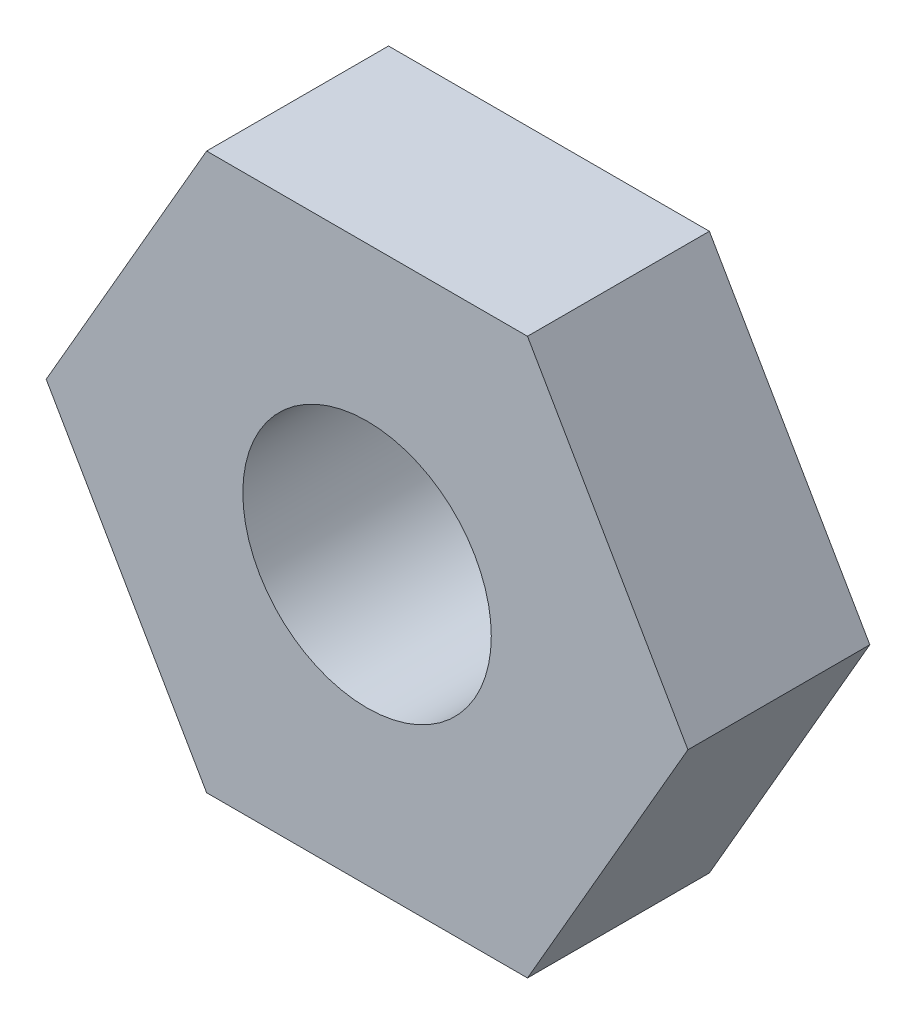
SolidWorks part; units mm, degrees
ref_plane "Front" through (0, 0, 0) normal (0, 0, 1) x (1, 0, 0)
ref_plane "Top" through (0, 0, 0) normal (0, 1, 0) x (1, 0, 0)
ref_plane "Right" through (0, 0, 0) normal (1, 0, 0) x (0, 0, -1)
sketch "Sketch1" plane through (0, 0, 0) normal (0, 0, 1) x (1, 0, 0)
  line L1 (1.5877, -2.75) -> (3.1754, 0)
  line L2 (3.1754, 0) -> (1.5877, 2.75)
  line L3 (1.5877, 2.75) -> (-1.5877, 2.75)
  line L4 (-1.5877, 2.75) -> (-3.1754, 0)
  line L5 (-3.1754, 0) -> (-1.5877, -2.75)
  line L6 (-1.5877, -2.75) -> (1.5877, -2.75)
  circle A0 centre (0, 0) radius 2.75 construction
  circle A1 centre (0, 0) radius 1.2295
  dimension "D1" = 2.459
  dimension "s" = 5.5
extrude "BaseNut" add sketch "Sketch1" against normal blind 1.8
cosmetic thread "ThreadCosmetic1" [suppressed] parameters "D2"=3
sketch "Sketch2" plane through (0, 0, 0) normal (0, 1, 0) x (1, 0, 0)
  line L0 (0, 7.0076) -> (0, -1.3024) construction
  line L1 (0.959, 1.9352) -> (1.2295, 1.9352)
  line L2 (1.2295, 1.9352) -> (1.4638, 1.8)
  line L3 (1.4638, 1.8) -> (1.2295, 1.6647)
  line L4 (1.2295, 1.6647) -> (0.959, 1.6647)
  line L5 (0.959, 1.6647) -> (0.959, 1.9352)
  line L6 (3.1754, 1.8) -> (1.5877, 1.8) construction
  dimension "D1" = 0.2705
  dimension "D2" = 2.459
revolve "Cut-Revolve10" [suppressed] cut sketch "Sketch2" angle 360 about L0
pattern_linear "LPattern10" [suppressed] count 6 spacing 0.3246 along (0, 0, 1)
equation "\"D1@Sketch2\" =  ( \"D2@ThreadCosmetic1\" - \"D1@Sketch1\" )  / 2"
equation "\"D2@Sketch2\" = \"D1@Sketch1\""
equation "\"D3@LPattern10\" = \"D1@Sketch2\" * 1.2"
equation "\"D1@LPattern10\" = \"m@BaseNut\" / \"D3@LPattern10\""
